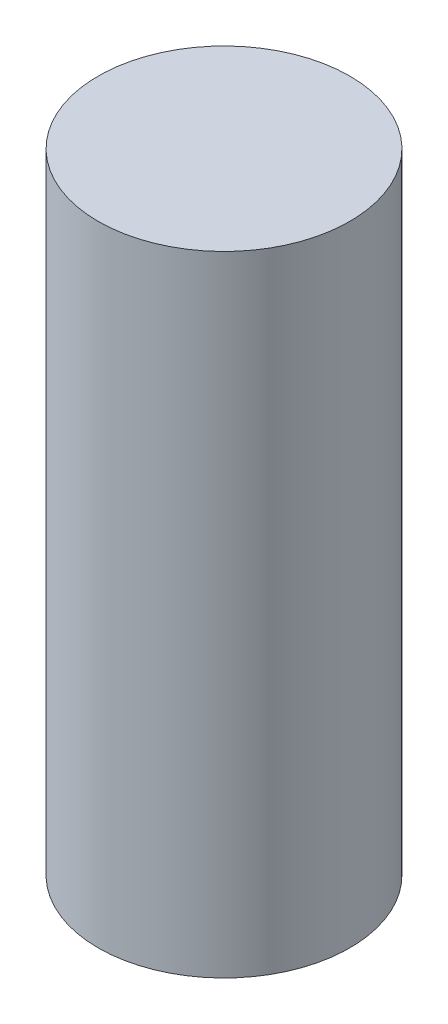
SolidWorks part; units mm, degrees
ref_plane "Ön Düzlem" through (0, 0, 0) normal (0, 0, 1) x (1, 0, 0)
ref_plane "Üst Düzlem" through (0, 0, 0) normal (0, 1, 0) x (1, 0, 0)
ref_plane "Sağ Düzlem" through (0, 0, 0) normal (1, 0, 0) x (0, 0, -1)
sketch "Sketch1" plane through (0, 0, 0) normal (0, 1, 0) x (1, 0, 0)
  circle A1 centre (-2.3084, 1.6469) radius 8
  dimension "D1" = 16
sketch "Sketch2" plane through (0, 0, 0) normal (0, 1, 0) x (1, 0, 0)
extrude "Boss-Extrude4" add sketch "Sketch1" along normal blind 40
